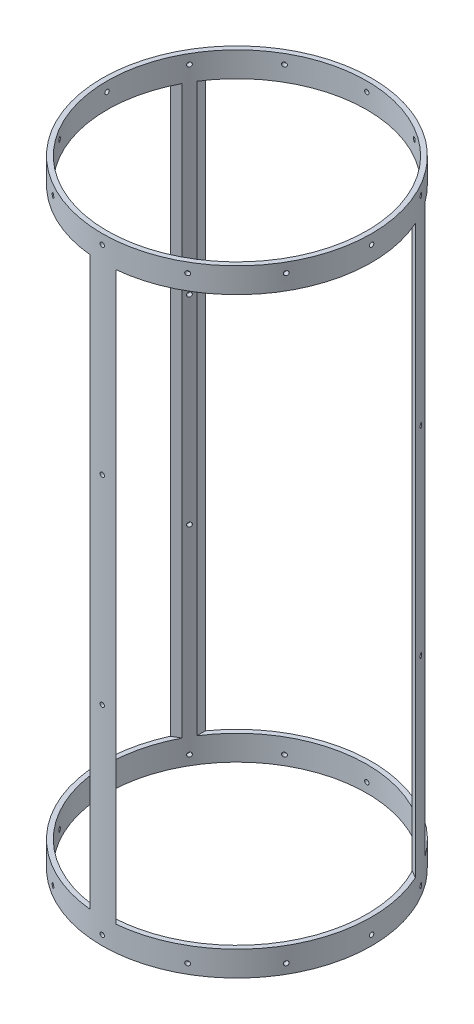
SolidWorks part; units mm, degrees
material "6061-T6 (SS)"
ref_plane "Front Plane" through (0, 0, 0) normal (0, 0, 1) x (1, 0, 0)
ref_plane "Top Plane" through (0, 0, 0) normal (0, 1, 0) x (1, 0, 0)
ref_plane "Right Plane" through (0, 0, 0) normal (1, 0, 0) x (0, 0, -1)
sketch "Sketch1" plane through (0, 0, 0) normal (0, 1, 0) x (1, 0, 0)
  circle A0 centre (0, 0) radius 88.9
  circle A1 centre (0, 0) radius 85.725
  dimension "D1" = 177.8
  dimension "D2" = 171.45
extrude "Boss-Extrude1" add sketch "Sketch1" along normal mid plane 407.162
sketch "Sketch2" plane through (0, 0, 0) normal (0, 0, 1) x (1, 0, 0)
  line L0 (85.725, 203.581) -> (-85.725, 203.581) construction
  line L1 (-72.39, -187.071) -> (72.39, -187.071)
  line L2 (-72.39, -187.071) -> (-72.39, 187.071)
  line L3 (-72.39, 187.071) -> (72.39, 187.071)
  line L4 (72.39, -187.071) -> (72.39, 187.071)
  line L5 (-72.39, -187.071) -> (72.39, 187.071) construction
  line L6 (-72.39, 187.071) -> (72.39, -187.071) construction
  line L7 (88.9, -203.581) -> (88.9, 203.581) construction
  point P0 (0, 0)
  dimension "D1" = 16.51
  dimension "D2" = 16.51
extrude "Cut-Extrude1" cut sketch "Sketch2" against normal up to surface (51.6033 mm away)
pattern_circular "CirPattern1" count 3 over 360 about axis through (0, 0, 0) along (0, 1, 0) of "Cut-Extrude1"
ref_plane "Plane1" through (88.9, 0, 0) normal (1, 0, 0) x (0, 0, -1)
sketch "Sketch4" plane through (88.9, 0, 0) normal (1, 0, 0) x (0, 0, -1)
  line L0 (0, 97.79) -> (0, -97.79) construction
  line L1 (88.9, 203.581) -> (-88.9, 203.581) construction
  circle A0 centre (0, 197.231) radius 1.4351
  dimension "D1" = 2.8702
  dimension "D2" = 6.35
extrude "Cut-Extrude3" cut sketch "Sketch4" against normal blind 15.24
pattern_circular "CirPattern3" count 12 over 360 about axis through (0, 203.581, 0) along (0, -1, 0) of "Cut-Extrude3"
mirror "Mirror1" about plane through (0, 0, 0) normal (0, 1, 0) of "Cut-Extrude3", "CirPattern3"
ref_plane "Plane2" through (0, 0, 88.9) normal (0, 0, 1) x (1, 0, 0)
sketch "Sketch5" plane through (0, 0, 88.9) normal (0, 0, 1) x (1, 0, 0)
  circle A0 centre (0, -65.7606) radius 1.4351
  circle A1 centre (0, 65.7606) radius 1.4351
  circle A2 centre (0, 197.231) radius 1.4351 construction
  circle A3 centre (0, -197.231) radius 1.4351 construction
  dimension "D1" = 131.4704
  dimension "D2" = 131.4704
  dimension "D3" = 2.8702
  dimension "D4" = 2.8702
extrude "Cut-Extrude4" cut sketch "Sketch5" against normal blind 46.482
pattern_circular "CirPattern4" count 3 over 360 about axis through (0, 203.581, 0) along (0, -1, 0) of "Cut-Extrude4"
